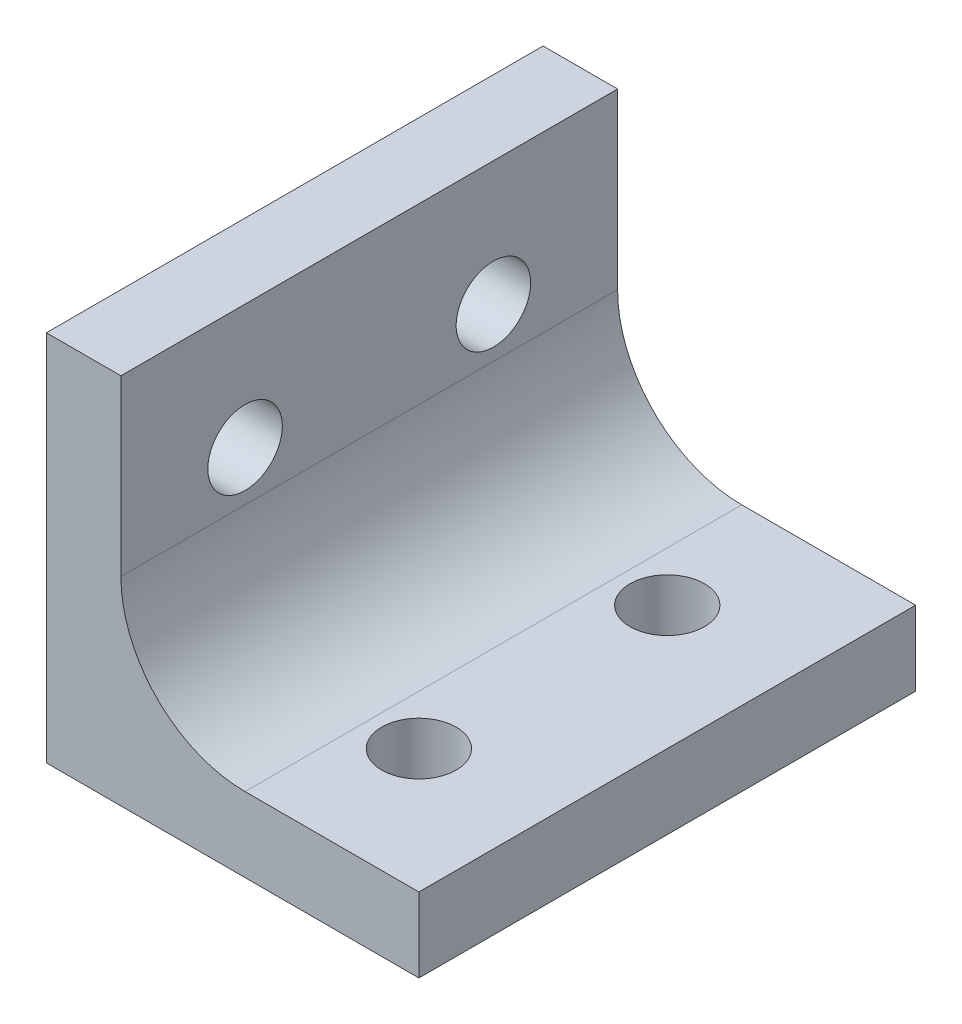
SolidWorks part; units mm, degrees
material "POM 乙缩醛共聚物"
ref_plane "前视基准面" through (0, 0, 0) normal (0, 0, 1) x (1, 0, 0)
ref_plane "上视基准面" through (0, 0, 0) normal (0, 1, 0) x (1, 0, 0)
ref_plane "右视基准面" through (0, 0, 0) normal (1, 0, 0) x (0, 0, -1)
sketch "草图1" plane through (0, 0, 0) normal (0, 1, 0) x (1, 0, 0)
  line L0 (0, 0) -> (0, -20)
  line L1 (0, -20) -> (15, -20)
  line L2 (15, -20) -> (15, 0)
  line L3 (15, 0) -> (0, 0)
extrude "凸台-拉伸1" add sketch "草图1" against normal blind 15
sketch "草图2" plane through (0, 0, 0) normal (0, 0, -1) x (-1, 0, 0)
  line L0 (-15, -12) -> (-3, -12)
  line L1 (-3, -12) -> (-3, 0)
  line L2 (-3, 0) -> (-15, 0)
  line L3 (-15, 0) -> (-15, -12)
extrude "切除-拉伸1" cut sketch "草图2" against normal through all
hole_wizard "Ø3.0 (3) 直径孔1" positions "草图4" profile "草图3" hole size "Ø3.0" standard "ANSI Metric"
sketch "草图4" plane through (3, 0, 0) normal (1, 0, 0) x (0, 0, -1)
  point P0 (-5, -5)
  point P1 (-15, -5)
sketch "草图3" plane through (3, -5, 5) normal (0, 1, 0) x (0, 0, -1)
  line L0 (0, 0) -> (0, 3)
  line L1 (0, 3) -> (1.5, 3)
  line L2 (1.5, 3) -> (1.5, 0)
  line L5 (1.5, 0) -> (0, 0)
  line L11 (0, -6.35) -> (0, 107.95) construction
  dimension "通孔孔直径" = 3
  dimension "通孔孔深度" = 3
hole_wizard "Ø3.0 (3) 直径孔2" positions "草图6" profile "草图5" hole size "Ø3.0" standard "ANSI Metric"
sketch "草图6" plane through (0, -12, 0) normal (0, 1, 0) x (1, 0, 0)
  point P0 (10, -5)
  point P1 (10, -15)
sketch "草图5" plane through (10, -12, 5) normal (1, 0, 0) x (0, 0, 1)
  line L0 (0, 0) -> (0, 3)
  line L1 (0, 3) -> (1.5, 3)
  line L2 (1.5, 3) -> (1.5, 0)
  line L5 (1.5, 0) -> (0, 0)
  line L11 (0, -6.35) -> (0, 107.95) construction
  dimension "通孔孔直径" = 3
  dimension "通孔孔深度" = 3
fillet "圆角1" radius 5 1 edges at (3, -12, 10)
